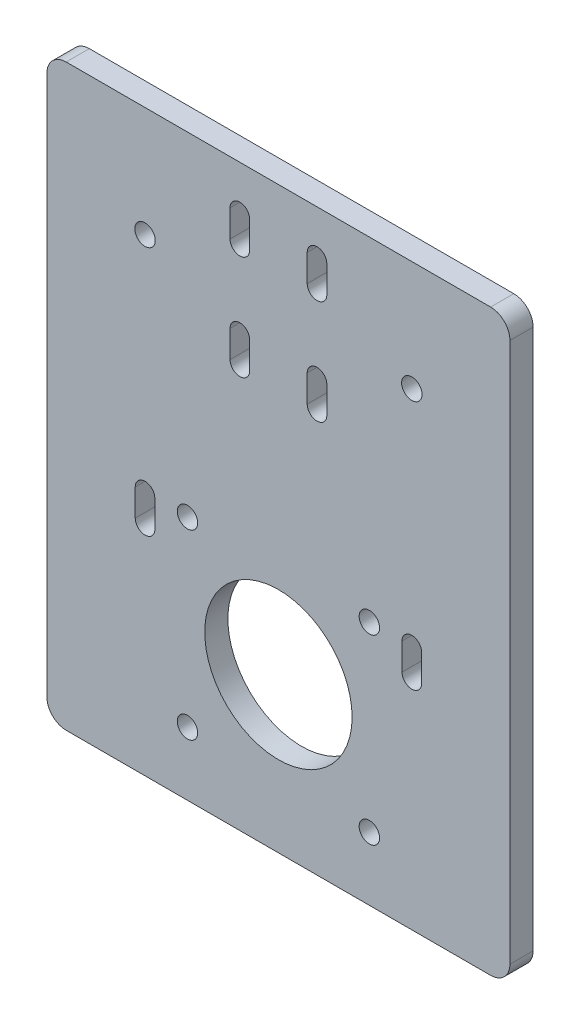
SolidWorks part; units mm, degrees
ref_plane "Front Plane" through (0, 0, 0) normal (0, 0, 1) x (1, 0, 0)
ref_plane "Top Plane" through (0, 0, 0) normal (0, 1, 0) x (1, 0, 0)
ref_plane "Right Plane" through (0, 0, 0) normal (1, 0, 0) x (0, 0, -1)
sketch "Sketch3" plane through (0, 0, 0) normal (0, 0, 1) x (1, 0, 0)
  line L1 (-55, -75) -> (55, -75)
  line L2 (-60, -70) -> (-60, 70)
  line L3 (-55, 75) -> (55, 75)
  line L4 (60, -70) -> (60, 70)
  line L5 (-60, -75) -> (60, 75) construction
  line L6 (-60, 75) -> (60, -75) construction
  arc A0 (-55, -75) -> (-60, -70) centre (-55, -70) cw
  arc A1 (55, -75) -> (60, -70) centre (55, -70) ccw
  arc A2 (55, 75) -> (60, 70) centre (55, 70) cw
  arc A3 (-60, 70) -> (-55, 75) centre (-55, 70) cw
  point P0 (0, 0)
  dimension "D3" = 5
  dimension "D1" = 120
  dimension "D2" = 150
extrude "Boss-Extrude1" add sketch "Sketch3" along normal blind 6
sketch "Sketch4" plane through (0, 0, 6) normal (0, 0, 1) x (1, 0, 0)
  line L0 (-55, -75) -> (55, -75) construction
  circle A0 centre (0, -35) radius 19.1
  point P2 (0, 0)
  dimension "D1" = 38.2
  dimension "D2" = 40
extrude "Cut-Extrude1" cut sketch "Sketch4" against normal blind 6
hole_wizard "M5 Clearance Hole1" positions "Sketch5" profile "Sketch6" hole size "M5" standard "ANSI Metric" end condition through all
sketch "Sketch5" plane through (0, 0, 6) normal (0, 0, 1) x (1, 0, 0)
  circle A0 centre (0, -35) radius 19.1 construction
  point P0 (-23.57, -11.43)
  point P2 (23.57, -11.43)
  point P4 (23.57, -58.57)
  point P6 (-23.57, -58.57)
  point P10 (0, 0)
  point P11 (0, 0)
  point P12 (0, 0)
  dimension "D2" = 23.57
  dimension "D3" = 23.57
  dimension "D5" = 23.57
  dimension "D1" = 47.14
  dimension "D4" = 23.57
sketch "Sketch6" plane through (-23.57, -11.43, 6) normal (1, 0, 0) x (0, -1, 0)
  line L0 (0, 0) -> (0, 6)
  line L1 (0, 6) -> (2.65, 6)
  line L2 (2.65, 6) -> (2.65, 0)
  line L5 (2.65, 0) -> (0, 0)
  line L11 (0, -6.35) -> (0, 107.95) construction
  dimension "Thru Hole Dia." = 5.3
  dimension "Thru Hole Depth" = 6
sketch "Sketch7" plane through (0, 0, 6) normal (0, 0, 1) x (1, 0, 0)
  line L0 (-34.57, -11.43) -> (-34.57, -18.43) construction
  line L1 (-32.03, -11.43) -> (-32.03, -18.43)
  line L2 (-37.11, -11.43) -> (-37.11, -18.43)
  line L3 (0, 37.3663) -> (0, -85.73) construction
  line L4 (34.57, -11.43) -> (34.57, -18.43) construction
  line L5 (32.03, -11.43) -> (32.03, -18.43)
  line L6 (37.11, -11.43) -> (37.11, -18.43)
  arc A0 (-32.03, -11.43) -> (-37.11, -11.43) centre (-34.57, -11.43) ccw
  arc A1 (-37.11, -18.43) -> (-32.03, -18.43) centre (-34.57, -18.43) ccw
  circle A2 centre (-23.57, -11.43) radius 2.65 construction
  arc A3 (32.03, -11.43) -> (37.11, -11.43) centre (34.57, -11.43) cw
  arc A4 (37.11, -18.43) -> (32.03, -18.43) centre (34.57, -18.43) cw
  point P2 (-34.57, -14.93)
  point P11 (34.57, -14.93)
  point P20 (0, 0)
  point P21 (0, 0)
  point P22 (0, 0)
  point P23 (0, 0)
  dimension "D1" = 2.54
  dimension "D2" = 7
  dimension "D3" = 11
extrude "Cut-Extrude2" cut sketch "Sketch7" against normal blind 6
hole_wizard "M5 Clearance Hole2" positions "Sketch8" profile "Sketch9" hole size "M5" standard "ANSI Metric" end condition through all
sketch "Sketch8" plane through (0, 0, 6) normal (0, 0, 1) x (1, 0, 0)
  point P0 (-34.57, 46.47)
  point P2 (34.57, 46.47)
  point P5 (0, 0)
  point P7 (0, 0)
  point P8 (0, 0)
  dimension "D1" = 61.4
sketch "Sketch9" plane through (-34.57, 46.47, 6) normal (1, 0, 0) x (0, -1, 0)
  line L0 (0, 0) -> (0, 6)
  line L1 (0, 6) -> (2.65, 6)
  line L2 (2.65, 6) -> (2.65, 0)
  line L5 (2.65, 0) -> (0, 0)
  line L11 (0, -6.35) -> (0, 107.95) construction
  dimension "Thru Hole Dia." = 5.3
  dimension "Thru Hole Depth" = 6
sketch "Sketch10" plane through (0, 0, 6) normal (0, 0, 1) x (1, 0, 0)
  line L0 (-10, 63.5) -> (-10, 56.5) construction
  line L1 (-7.46, 63.5) -> (-7.46, 56.5)
  line L2 (-12.54, 63.5) -> (-12.54, 56.5)
  line L3 (10, 63.5) -> (10, 56.5) construction
  line L4 (12.54, 63.5) -> (12.54, 56.5)
  line L5 (7.46, 63.5) -> (7.46, 56.5)
  line L6 (55, 75) -> (-55, 75) construction
  line L7 (34.57, 46.47) -> (-34.57, 46.47) construction
  line L8 (0, 37.3663) -> (0, -85.73) construction
  line L9 (-10, 29.44) -> (-10, 36.44) construction
  line L10 (-7.46, 29.44) -> (-7.46, 36.44)
  line L11 (-12.54, 29.44) -> (-12.54, 36.44)
  line L12 (10, 29.44) -> (10, 36.44) construction
  line L13 (12.54, 29.44) -> (12.54, 36.44)
  line L14 (7.46, 29.44) -> (7.46, 36.44)
  arc A0 (-7.46, 63.5) -> (-12.54, 63.5) centre (-10, 63.5) ccw
  arc A1 (-12.54, 56.5) -> (-7.46, 56.5) centre (-10, 56.5) ccw
  arc A2 (12.54, 63.5) -> (7.46, 63.5) centre (10, 63.5) ccw
  arc A3 (7.46, 56.5) -> (12.54, 56.5) centre (10, 56.5) ccw
  arc A4 (-7.46, 29.44) -> (-12.54, 29.44) centre (-10, 29.44) cw
  arc A5 (-12.54, 36.44) -> (-7.46, 36.44) centre (-10, 36.44) cw
  arc A6 (12.54, 29.44) -> (7.46, 29.44) centre (10, 29.44) cw
  arc A7 (7.46, 36.44) -> (12.54, 36.44) centre (10, 36.44) cw
  point P2 (-10, 60)
  point P7 (10, 60)
  point P21 (0, 0)
  point P22 (-34.57, 46.47)
  point P24 (34.57, 46.47)
  point P28 (-10, 32.94)
  point P35 (10, 32.94)
  dimension "D1" = 2.54
  dimension "D2" = 7
  dimension "D3" = 15
  dimension "D4" = 20
  dimension "D5" = 10
extrude "Cut-Extrude3" cut sketch "Sketch10" against normal blind 6
sketch "Sketch11" plane through (0, 0, 0) normal (0, 0, -1) x (-1, 0, 0)
  line L0 (-41.0184, 46.47) -> (71.6367, 46.47) construction
